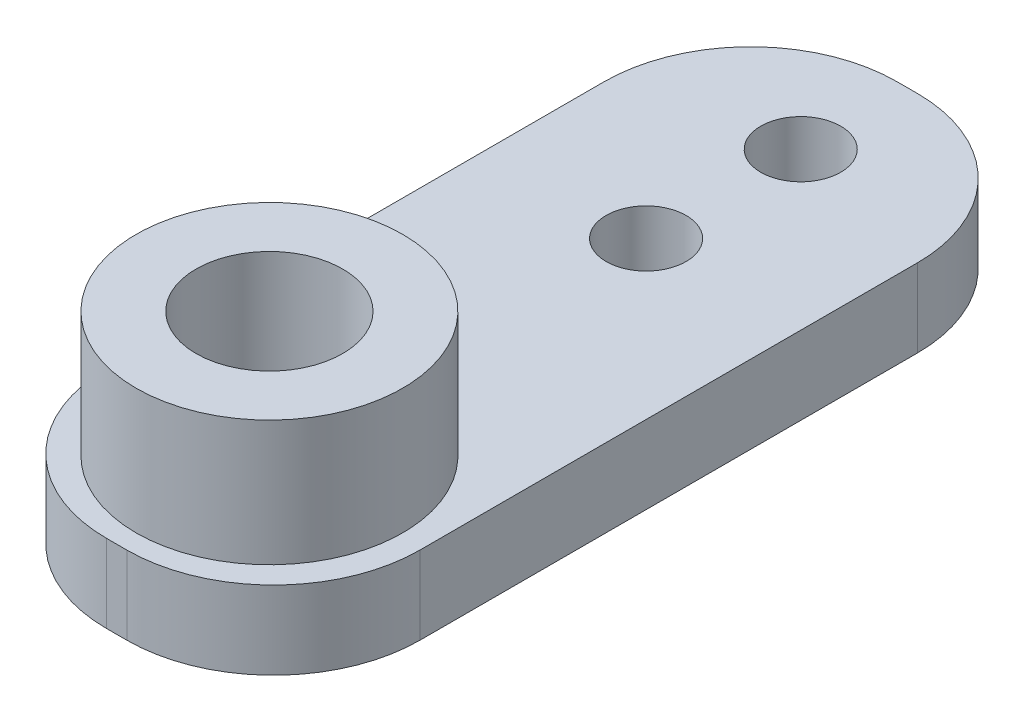
SolidWorks part; units mm, degrees
ref_plane "Front Plane" through (0, 0, 0) normal (0, 0, 1) x (1, 0, 0)
ref_plane "Top Plane" through (0, 0, 0) normal (0, 1, 0) x (1, 0, 0)
ref_plane "Right Plane" through (0, 0, 0) normal (1, 0, 0) x (0, 0, -1)
sketch "Sketch1" plane through (0, 0, 0) normal (0, 1, 0) x (1, 0, 0)
  line L1 (-5.5, 0) -> (-6.26, 0)
  line L2 (0, -5.5) -> (0, -24.16)
  line L3 (-5.5, -29.66) -> (-6.26, -29.66)
  line L4 (-11.76, -5.5) -> (-11.76, -24.16)
  arc A0 (-11.76, -24.16) -> (-6.26, -29.66) centre (-6.26, -24.16) ccw
  arc A1 (-5.5, -29.66) -> (0, -24.16) centre (-5.5, -24.16) ccw
  arc A2 (0, -5.5) -> (-5.5, 0) centre (-5.5, -5.5) ccw
  arc A3 (-11.76, -5.5) -> (-6.26, 0) centre (-6.26, -5.5) cw
  point P7 (-11.76, -29.66)
  point P12 (0, 0)
  point P15 (-11.76, 0)
  dimension "D3" = 5.5
  dimension "D1" = 11.76
  dimension "D2" = 29.66
extrude "Boss-Extrude1" add sketch "Sketch1" along normal blind 2.93
sketch "Sketch2" plane through (0, 2.93, 0) normal (0, 1, 0) x (1, 0, 0)
  line L0 (-6.26, -29.66) -> (-5.5, -29.66) construction
  circle A0 centre (-5.88, -23.93) radius 5
  point P0 (-5.88, -23.93)
  point P3 (-5.88, -29.66)
  dimension "D3" = 10
  dimension "D1" = 0
  dimension "D2" = 5.73
extrude "Boss-Extrude2" add sketch "Sketch2" along normal blind 4.7
sketch "Sketch3" plane through (0, 7.63, 0) normal (0, 1, 0) x (1, 0, 0)
  circle A0 centre (-5.88, -23.93) radius 2.75
  dimension "D1" = 5.5
extrude "Cut-Extrude1" cut sketch "Sketch3" against normal up to next
sketch "Sketch4" plane through (0, 2.93, 0) normal (0, 1, 0) x (1, 0, 0)
  line L0 (-5.88, 0) -> (-5.88, -16.2257) construction
  line L1 (-5.5, 0) -> (-6.26, 0) construction
  circle A0 centre (-5.88, -4) radius 1.5
  circle A1 centre (-5.88, -9.8) radius 1.5
  dimension "D1" = 3
  dimension "D2" = 3
  dimension "D3" = 5.8
  dimension "D4" = 4
extrude "Cut-Extrude2" cut sketch "Sketch4" against normal up to next
